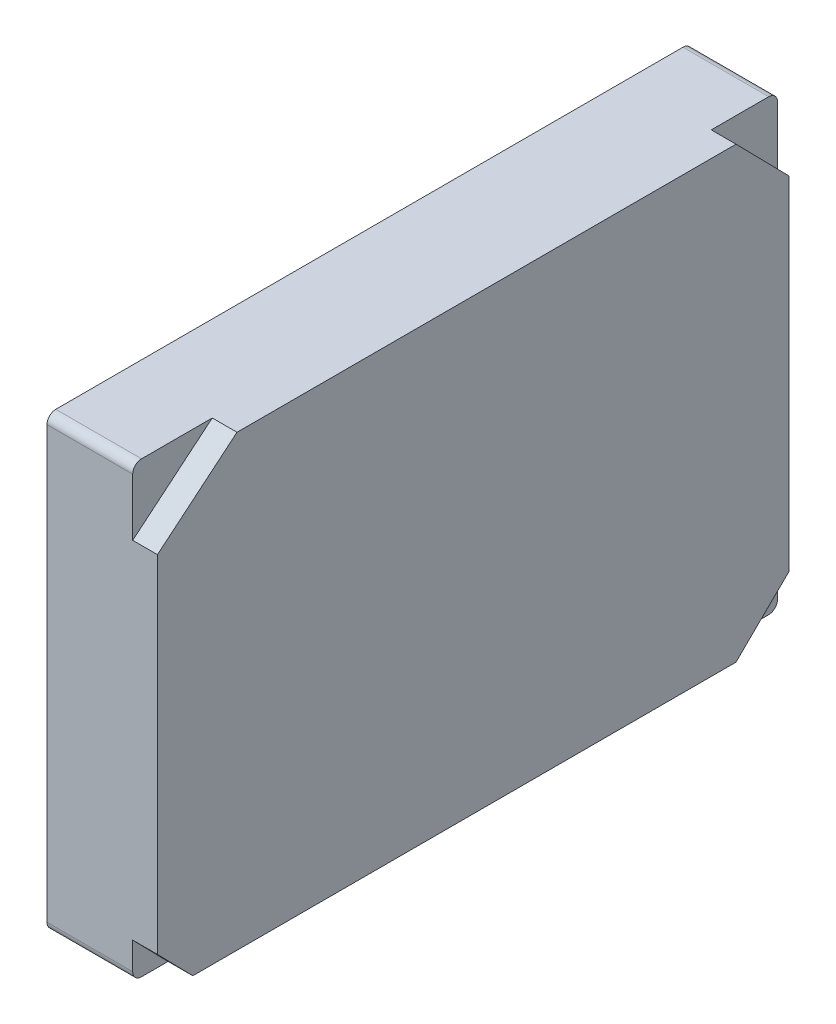
SolidWorks part; units mm, degrees
ref_plane "Front Plane" through (0, 0, 0) normal (0, 0, 1) x (1, 0, 0)
ref_plane "Top Plane" through (0, 0, 0) normal (0, 1, 0) x (1, 0, 0)
ref_plane "Right Plane" through (0, 0, 0) normal (1, 0, 0) x (0, 0, -1)
sketch "Sketch1" plane through (0, 0, 0) normal (1, 0, 0) x (0, 0, -1)
  line L1 (-63.5908, 30.7923) -> (82.3092, 30.7923)
  line L2 (-63.5908, 30.7923) -> (-63.5908, -70.7077)
  line L3 (-63.5908, -70.7077) -> (82.3092, -70.7077)
  line L4 (82.3092, 30.7923) -> (82.3092, -70.7077)
  dimension "D1" = 145.9
  dimension "D2" = 101.5
extrude "Boss-Extrude1" add sketch "Sketch1" along normal blind 25
sketch "Sketch2" plane through (25, 0, 0) normal (1, 0, 0) x (0, 0, -1)
  line L0 (67.3092, 30.7923) -> (79.3092, 18.5667)
  line L1 (82.3092, 30.7923) -> (-63.5908, 30.7923) construction
  line L2 (79.3092, 18.5667) -> (79.3092, -58.9291)
  line L3 (79.3092, -58.9291) -> (67.3092, -70.7077)
  line L4 (-63.5908, -70.7077) -> (82.3092, -70.7077) construction
  line L5 (67.3092, -70.7077) -> (82.3092, -70.7077)
  line L6 (82.3092, -70.7077) -> (82.3092, 30.7923)
  line L7 (82.3092, 30.7923) -> (67.3092, 30.7923)
  line L8 (-45.5908, 30.7923) -> (-63.5908, 15.816)
  line L9 (-63.5908, 30.7923) -> (-63.5908, -70.7077) construction
  line L10 (-63.5908, 15.816) -> (-63.5908, 30.7923)
  line L11 (-63.5908, 30.7923) -> (-45.5908, 30.7923)
  line L12 (-63.5908, -62.5191) -> (-55.5908, -70.7077)
  line L13 (-55.5908, -70.7077) -> (-63.5908, -70.7077)
  line L14 (-63.5908, -70.7077) -> (-63.5908, -62.5191)
  dimension "D1" = 15
  dimension "D2" = 3
  dimension "D3" = 18
  dimension "D4" = 8
extrude "Cut-Extrude1" cut sketch "Sketch2" against normal blind 5.6
fillet "Fillet1" radius 2 4 edges at (9.7, -70.7077, -82.3092) (9.7, 30.7923, -82.3092) (9.7, -70.7077, 63.5908) (9.7, 30.7923, 63.5908)
sketch "Sketch3" plane through (0, 0, 0) normal (-1, 0, 0) x (0, 0, 1)
  line L0 (61.5908, -70.7077) -> (-80.3092, -70.7077) construction
  circle A0 centre (-64.0006, 27.7923) radius 1.5
  circle A1 centre (12.4994, 27.7923) radius 1.5
  circle A2 centre (-64.0006, -67.7077) radius 1.5
  circle A3 centre (12.4994, -67.7077) radius 1.5
  point P8 (-64.0006, 29.2923)
  point P9 (-62.5006, 27.7923)
  point P10 (10.9994, 27.7923)
  point P11 (-64.0006, -69.2077)
  point P12 (-62.5006, -67.7077)
  point P13 (12.4994, -69.2077)
  point P14 (10.9994, -67.7077)
  dimension "D1" = 3
  dimension "D2" = 1.5
  dimension "D3" = 1.5
  dimension "D4" = 73.5
extrude "Cut-Extrude2" cut sketch "Sketch3" against normal blind 5
sketch "Sketch4" plane through (0, 0, -82.3092) normal (0, 0, -1) x (-1, 0, 0)
  line L0 (0, -68.7077) -> (0, 28.7923) construction
  line L1 (-7.2, -66.101) -> (-2, -66.101)
  line L2 (-7.2, -66.101) -> (-7.2, -64.7077)
  line L3 (-7.2, -64.7077) -> (-2, -64.7077)
  line L4 (-2, -66.101) -> (-2, -64.7077)
  line L5 (-7.2, 24.7923) -> (-2, 24.7923)
  line L6 (-7.2, 24.7923) -> (-7.2, 25.7498)
  line L7 (-7.2, 25.7498) -> (-2, 25.7498)
  line L8 (-2, 24.7923) -> (-2, 25.7498)
  line L9 (0, -70.7077) -> (-19.4, -70.7077) construction
  line L10 (-19.4, 30.7923) -> (0, 30.7923) construction
  dimension "D1" = 5.2
  dimension "D2" = 2
  dimension "D3" = 6
  dimension "D4" = 6
extrude "Cut-Extrude3" cut sketch "Sketch4" against normal blind 3
sketch "Sketch5" plane through (0, 0, -82.3092) normal (0, 0, -1) x (-1, 0, 0)
  line L0 (0, -41.5324) -> (-0.8, -41.5324)
  line L1 (0, -68.7077) -> (0, 28.7923) construction
  line L2 (-0.8, -41.5324) -> (-0.8, -21.9077)
  line L3 (-0.8, -21.9077) -> (-4, -21.9077)
  line L4 (-4, -21.9077) -> (-4, -24.1077)
  line L5 (-4, -24.1077) -> (-5.4, -24.1077)
  line L6 (-5.4, -24.1077) -> (-5.4, -61.1077)
  line L7 (-5.4, -61.1077) -> (-0.8, -61.1077)
  line L8 (-0.8, -61.1077) -> (-0.8, -63.3077)
  line L9 (-0.8, -63.3077) -> (0, -63.3077)
  line L10 (0, -41.5324) -> (0, -63.3077)
  line L11 (-2, -64.7077) -> (-7.2, -64.7077) construction
  dimension "D1" = 0.8
  dimension "D2" = 3.2
  dimension "D3" = 1.4
  dimension "D4" = 2.2
  dimension "D5" = 2.2
  dimension "D6" = 37
  dimension "D7" = 1.4
extrude "Cut-Extrude4" cut sketch "Sketch5" against normal blind 4
